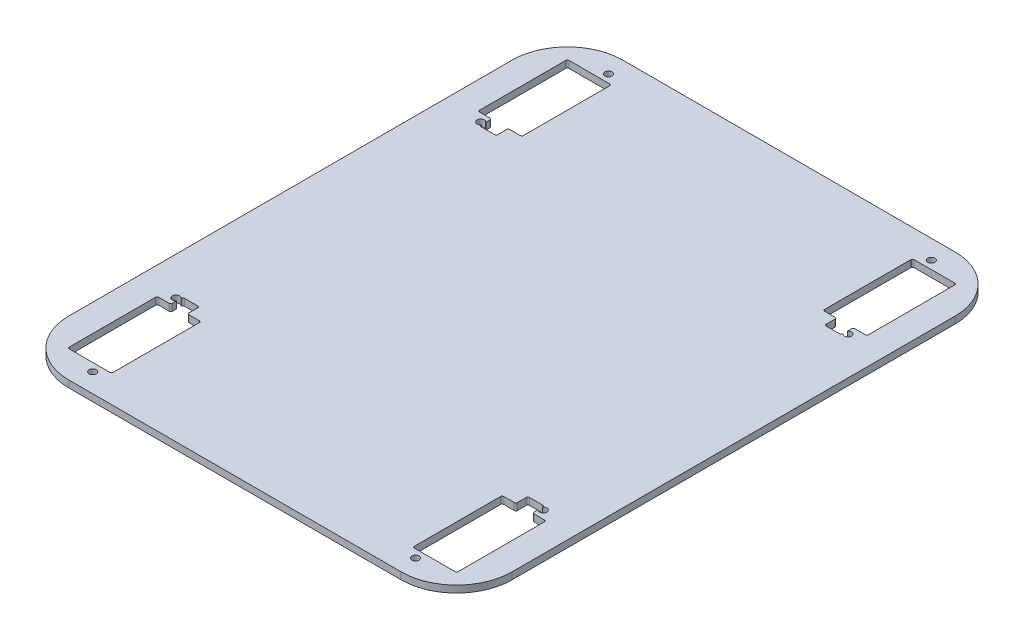
SolidWorks part; units mm, degrees
material "Plain Carbon Steel"
ref_plane "Front" through (0, 0, 0) normal (0, 0, 1) x (1, 0, 0)
ref_plane "Top" through (0, 0, 0) normal (0, 1, 0) x (1, 0, 0)
ref_plane "Right" through (0, 0, 0) normal (1, 0, 0) x (0, 0, -1)
sketch "Sketch1" plane through (0, 0, 0) normal (0, 1, 0) x (1, 0, 0)
  line L1 (-101.6, -127) -> (101.6, -127)
  line L2 (-101.6, -127) -> (-101.6, 127)
  line L3 (-101.6, 127) -> (101.6, 127)
  line L4 (101.6, -127) -> (101.6, 127)
  line L5 (-101.6, -127) -> (101.6, 127) construction
  line L6 (-101.6, 127) -> (101.6, -127) construction
  point P0 (0, 0)
  dimension "D1" = 254
  dimension "D2" = 203.2
extrude "Boss-Extrude1" add sketch "Sketch1" along normal blind 3.175
fillet "Fillet1" radius 25.4 4 edges at (-101.6, 1.5875, -127) (-101.6, 1.5875, 127) (101.6, 1.5875, -127) (101.6, 1.5875, 127)
sketch "Sketch2" plane through (0, 0, 0) normal (0, -1, 0) x (1, 0, 0)
  line L12 (-69.3, 73.8) -> (-69.3, 114.3) construction
  line L13 (-75.55, 73.8) -> (-69.3, 73.8) construction
  line L14 (-82.65, 73.8) -> (-82.65, 68.3) construction
  line L15 (-75.55, 73.8) -> (-75.55, 68.3) construction
  line L16 (-79.1, 114.3) -> (-79.1, 68.3) construction
  line L18 (-75.55, 68.3) -> (-82.65, 68.3) construction
  line L21 (-88.9, 73.8) -> (-82.65, 73.8) construction
  line L22 (-88.9, 114.3) -> (-88.9, 73.8) construction
  line L23 (-69.3, 114.3) -> (-88.9, 114.3) construction
  line L25 (-76.2, 127) -> (76.2, 127) construction
  line L26 (-101.6, -101.6) -> (-101.6, 101.6) construction
  line L27 (-69.046, 73.546) -> (-69.046, 114.554)
  line L28 (-69.046, 114.554) -> (-89.154, 114.554)
  line L29 (-89.154, 114.554) -> (-89.154, 73.546)
  line L30 (-89.154, 73.546) -> (-82.904, 73.546)
  line L31 (-82.904, 73.546) -> (-82.904, 68.046)
  line L32 (-75.296, 68.046) -> (-82.904, 68.046)
  line L33 (-75.296, 73.546) -> (-75.296, 68.046)
  line L34 (-75.296, 73.546) -> (-69.046, 73.546)
  line L35 (0, -127) -> (0, 127) construction
  line L36 (76.2, -127) -> (-76.2, -127) construction
  line L37 (-101.6, 0) -> (101.6, 0) construction
  line L38 (101.6, 101.6) -> (101.6, -101.6) construction
  line L39 (69.3, 114.3) -> (88.9, 114.3) construction
  line L40 (88.9, 114.3) -> (88.9, 73.8) construction
  line L41 (88.9, 73.8) -> (82.65, 73.8) construction
  line L42 (75.55, 68.3) -> (82.65, 68.3) construction
  line L43 (79.1, 114.3) -> (79.1, 68.3) construction
  line L44 (75.55, 73.8) -> (75.55, 68.3) construction
  line L45 (82.65, 73.8) -> (82.65, 68.3) construction
  line L46 (75.55, 73.8) -> (69.3, 73.8) construction
  line L47 (69.3, 73.8) -> (69.3, 114.3) construction
  line L48 (75.296, 73.546) -> (69.046, 73.546)
  line L49 (75.296, 73.546) -> (75.296, 68.046)
  line L50 (75.296, 68.046) -> (82.904, 68.046)
  line L51 (82.904, 73.546) -> (82.904, 68.046)
  line L52 (89.154, 73.546) -> (82.904, 73.546)
  line L53 (89.154, 114.554) -> (89.154, 73.546)
  line L54 (69.046, 114.554) -> (89.154, 114.554)
  line L55 (69.046, 73.546) -> (69.046, 114.554)
  line L56 (69.3, -73.8) -> (69.3, -114.3) construction
  line L57 (75.55, -73.8) -> (69.3, -73.8) construction
  line L58 (82.65, -73.8) -> (82.65, -68.3) construction
  line L59 (75.55, -73.8) -> (75.55, -68.3) construction
  line L60 (79.1, -114.3) -> (79.1, -68.3) construction
  line L61 (75.55, -68.3) -> (82.65, -68.3) construction
  line L62 (88.9, -73.8) -> (82.65, -73.8) construction
  line L63 (88.9, -114.3) -> (88.9, -73.8) construction
  line L64 (69.3, -114.3) -> (88.9, -114.3) construction
  line L65 (-69.3, -114.3) -> (-88.9, -114.3) construction
  line L66 (-88.9, -114.3) -> (-88.9, -73.8) construction
  line L67 (-88.9, -73.8) -> (-82.65, -73.8) construction
  line L68 (-75.55, -68.3) -> (-82.65, -68.3) construction
  line L69 (-79.1, -114.3) -> (-79.1, -68.3) construction
  line L70 (-75.55, -73.8) -> (-75.55, -68.3) construction
  line L71 (-82.65, -73.8) -> (-82.65, -68.3) construction
  line L72 (-75.55, -73.8) -> (-69.3, -73.8) construction
  line L73 (-69.3, -73.8) -> (-69.3, -114.3) construction
  line L74 (69.046, -73.546) -> (69.046, -114.554)
  line L75 (69.046, -114.554) -> (89.154, -114.554)
  line L76 (89.154, -114.554) -> (89.154, -73.546)
  line L77 (89.154, -73.546) -> (82.904, -73.546)
  line L78 (82.904, -73.546) -> (82.904, -68.046)
  line L79 (75.296, -68.046) -> (82.904, -68.046)
  line L80 (75.296, -73.546) -> (75.296, -68.046)
  line L81 (75.296, -73.546) -> (69.046, -73.546)
  line L82 (-75.296, -73.546) -> (-69.046, -73.546)
  line L83 (-75.296, -73.546) -> (-75.296, -68.046)
  line L84 (-75.296, -68.046) -> (-82.904, -68.046)
  line L85 (-82.904, -73.546) -> (-82.904, -68.046)
  line L86 (-89.154, -73.546) -> (-82.904, -73.546)
  line L87 (-89.154, -114.554) -> (-89.154, -73.546)
  line L88 (-69.046, -114.554) -> (-89.154, -114.554)
  line L89 (-69.046, -73.546) -> (-69.046, -114.554)
  dimension "D1" = 19.6
  dimension "D2" = 7.1
  dimension "D3" = 5.5
  dimension "D4" = 40.5
  dimension "D5" = 12.7
  dimension "D6" = 12.7
  dimension "D7" = 0.254
extrude "Cut-Extrude1" cut sketch "Sketch2" against normal blind 25.4
fillet "Fillet2" radius 0.762 32 edges at (-69.046, 1.5875, 114.554) (-89.154, 1.5875, 114.554) (-89.154, 1.5875, 73.546) (-82.904, 1.5875, 68.046) (-82.904, 1.5875, 73.546) (-69.046, 1.5875, 73.546) (-75.296, 1.5875, 73.546) (-75.296, 1.5875, 68.046) (75.296, 1.5875, 68.046) (75.296, 1.5875, 73.546) (69.046, 1.5875, 73.546) (69.046, 1.5875, 114.554) (89.154, 1.5875, 114.554) (89.154, 1.5875, 73.546) (82.904, 1.5875, 73.546) (82.904, 1.5875, 68.046) (75.296, 1.5875, -68.046) (69.046, 1.5875, -73.546) (75.296, 1.5875, -73.546) (82.904, 1.5875, -68.046) (82.904, 1.5875, -73.546) (89.154, 1.5875, -73.546) (69.046, 1.5875, -114.554) (89.154, 1.5875, -114.554) (-89.154, 1.5875, -73.546) (-82.904, 1.5875, -73.546) (-82.904, 1.5875, -68.046) (-75.296, 1.5875, -68.046) (-75.296, 1.5875, -73.546) (-69.046, 1.5875, -73.546) (-69.046, 1.5875, -114.554) (-89.154, 1.5875, -114.554)
hole_wizard "M4x0.7 Tapped Hole3" positions "Sketch8" profile "Sketch9" tap size "M4x0.7" standard "ANSI Metric" end condition through all
sketch "Sketch8" plane through (0, 3.175, 0) normal (0, 1, 0) x (1, 0, 0)
  line L1 (0, 168.1772) -> (0, -235.624) construction
  line L3 (-191.387, 0) -> (212.4142, 0) construction
  point P0 (-84.2, -69.85)
  point P3 (-74, -118.25)
  point P20 (74, -118.25)
  point P21 (84.2, -69.85)
  point P22 (84.2, 69.85)
  point P23 (74, 118.25)
  point P24 (-74, 118.25)
  point P25 (-84.2, 69.85)
  dimension "D1" = 84.2
  dimension "D2" = 69.85
  dimension "D3" = 48.4
  dimension "D4" = 10.2
sketch "Sketch9" plane through (-84.2, 3.175, 69.85) normal (1, 0, 0) x (0, 0, 1)
  line L0 (0, 0) -> (0, 3.175)
  line L1 (0, 3.175) -> (1.65, 3.175)
  line L2 (1.65, 3.175) -> (1.65, 0)
  line L5 (1.65, 0) -> (0, 0)
  line L11 (0, -6.35) -> (0, 107.95) construction
  dimension "Thru Tap Drill Dia." = 3.3
  dimension "Thru Tap Drill Depth" = 3.175
cosmetic thread "Hole Thread11" parameters "D2"=4
cosmetic thread "Hole Thread12" parameters "D2"=4
cosmetic thread "Hole Thread13" parameters "D2"=4
cosmetic thread "Hole Thread14" parameters "D2"=4
cosmetic thread "Hole Thread15" parameters "D2"=4
cosmetic thread "Hole Thread16" parameters "D2"=4
cosmetic thread "Hole Thread17" parameters "D2"=4
cosmetic thread "Hole Thread18" parameters "D2"=4
